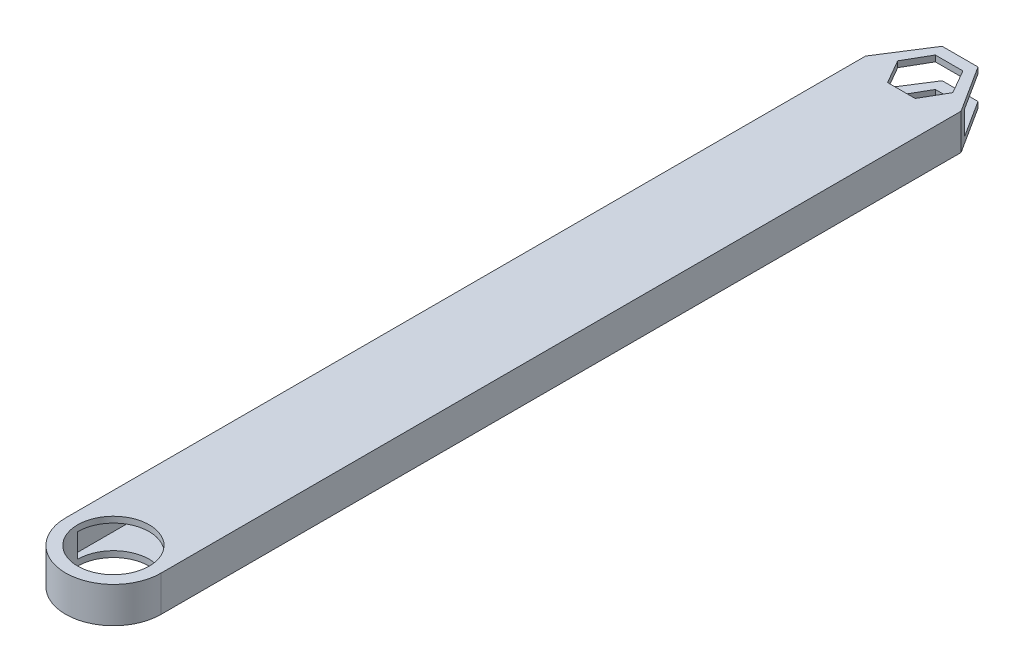
SolidWorks part; units mm, degrees
material "6061 Alloy"
ref_plane "Front Plane" through (0, 0, 0) normal (0, 0, 1) x (1, 0, 0)
ref_plane "Top Plane" through (0, 0, 0) normal (0, 1, 0) x (1, 0, 0)
ref_plane "Right Plane" through (0, 0, 0) normal (1, 0, 0) x (0, 0, -1)
sketch "Sketch1" plane through (0, 0, 0) normal (0, 0, 1) x (1, 0, 0)
  line L1 (0, 0) -> (25.4, 0)
  line L2 (0, 0) -> (0, 9.525)
  line L3 (0, 9.525) -> (25.4, 9.525)
  line L4 (25.4, 0) -> (25.4, 9.525)
  dimension "D1" = 25.4
  dimension "D2" = 9.525
extrude "Boss-Extrude1" add sketch "Sketch1" along normal blind 228.6
sketch "Sketch2" plane through (0, 0, 228.6) normal (0, 0, 1) x (1, 0, 0)
  line L4 (23.8125, 1.5875) -> (23.8125, 7.9375)
  line L5 (23.8125, 1.5875) -> (23.8125, 7.9375)
  line L6 (1.5875, 7.9375) -> (1.5875, 1.5875)
  line L7 (1.5875, 7.9375) -> (1.5875, 1.5875)
  line L8 (23.8125, 7.9375) -> (1.5875, 7.9375)
  line L9 (1.5875, 1.5875) -> (23.8125, 1.5875)
  line L10 (23.8125, 7.9375) -> (1.5875, 7.9375)
  line L13 (1.5875, 1.5875) -> (23.8125, 1.5875)
  dimension "D1" = 1.5875
extrude "Cut-Extrude1" cut sketch "Sketch2" against normal through all
sketch "Sketch3" plane through (0, 0, 0) normal (0, -1, 0) x (1, 0, 0)
  line L3 (20.0323, 12.7) -> (16.3662, 19.05)
  line L4 (16.3662, 19.05) -> (9.0338, 19.05)
  line L5 (9.0338, 19.05) -> (5.3677, 12.7)
  line L6 (5.3677, 12.7) -> (9.0338, 6.35)
  line L7 (9.0338, 6.35) -> (16.3662, 6.35)
  line L8 (16.3662, 6.35) -> (20.0323, 12.7)
  line L9 (25.4, 228.6) -> (25.4, 0) construction
  line L10 (0, 0) -> (25.4, 0) construction
  circle A0 centre (12.7, 12.7) radius 6.35 construction
  dimension "D3" = 12.7
  dimension "D1" = 12.7
  dimension "D2" = 12.7
extrude "Cut-Extrude2" cut sketch "Sketch3" against normal through all
sketch "Sketch4" plane through (0, 9.525, 0) normal (0, 1, 0) x (1, 0, 0)
  line L0 (25.4, -15.875) -> (17.4625, -3.4325)
  line L1 (25.4, -228.6) -> (25.4, 0) construction
  line L2 (17.4625, -3.4325) -> (7.9375, -3.4325)
  line L3 (7.9375, -3.4325) -> (0, -15.875)
  line L4 (0, -228.6) -> (0, 0) construction
  line L5 (0, -15.875) -> (0, 0)
  line L6 (0, 0) -> (25.4, 0)
  line L7 (25.4, 0) -> (0, 0) construction
  line L8 (25.4, 0) -> (25.4, -15.875)
  line L9 (9.0338, -6.35) -> (16.3662, -6.35) construction
  point P13 (12.7, -6.35)
  point P16 (12.7, -3.4325)
  dimension "D1" = 9.525
  dimension "D2" = 2.9175
  dimension "D3" = 15.875
  dimension "D4" = 15.875
extrude "Cut-Extrude3" cut sketch "Sketch4" against normal through all
sketch "Sketch5" plane through (0, 9.525, 0) normal (0, 1, 0) x (1, 0, 0)
  line L0 (25.4, -228.6) -> (0, -228.6) construction
  line L1 (0, -228.6) -> (25.4, -228.6)
  arc A0 (0, -228.6) -> (25.4, -228.6) centre (12.7, -228.6) ccw
extrude "Boss-Extrude2" add sketch "Sketch5" against normal blind 9.525
sketch "Sketch6" plane through (0, 9.525, 0) normal (0, 1, 0) x (1, 0, 0)
  circle A0 centre (12.7, -228.6) radius 9.525
  dimension "D1" = 19.05
extrude "Cut-Extrude4" cut sketch "Sketch6" against normal blind 9.525
